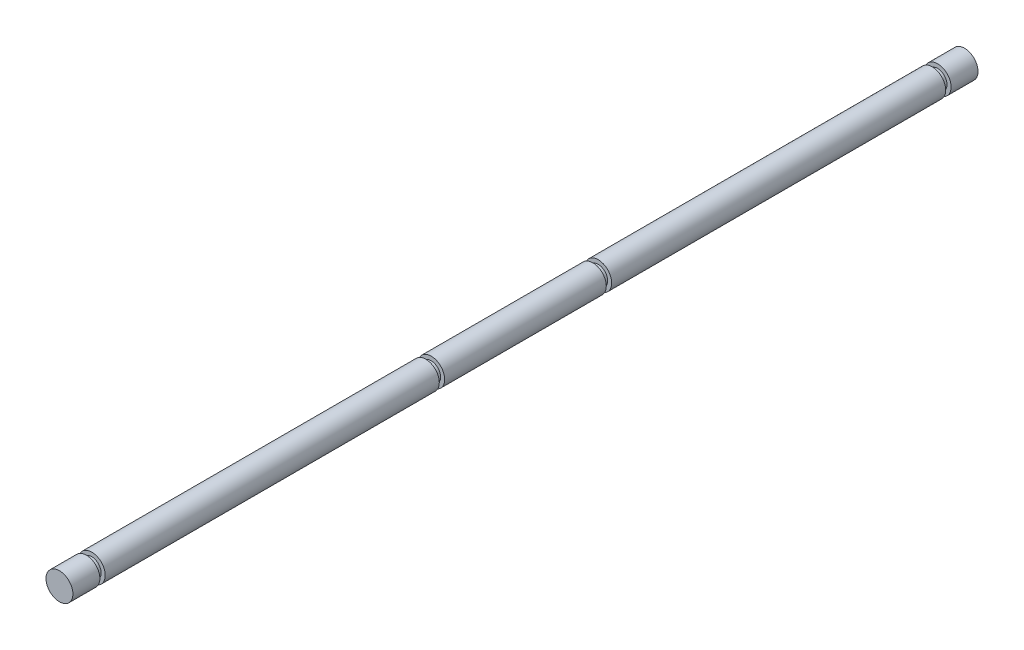
SolidWorks part; units mm, degrees
ref_plane "前视基准面" through (0, 0, 0) normal (0, 0, 1) x (1, 0, 0)
ref_plane "上视基准面" through (0, 0, 0) normal (0, 1, 0) x (1, 0, 0)
ref_plane "右视基准面" through (0, 0, 0) normal (1, 0, 0) x (0, 0, -1)
sketch "草图1" plane through (0, 0, 0) normal (0, 0, 1) x (1, 0, 0)
  circle A0 centre (0, 0) radius 5
  dimension "D1" = 10
extrude "凸台-拉伸1" add sketch "草图1" along normal blind 60
sketch "草图2" plane through (0, 0, 60) normal (0, 0, 1) x (1, 0, 0)
  circle A0 centre (0, 0) radius 3.5
  dimension "D1" = 7
extrude "凸台-拉伸2" add sketch "草图2" along normal blind 2
sketch "草图3" plane through (0, 0, 0) normal (0, 0, -1) x (-1, 0, 0)
  circle A0 centre (0, 0) radius 3.5
  dimension "D1" = 7
extrude "凸台-拉伸3" add sketch "草图3" along normal blind 2
sketch "草图4" plane through (0, 0, -2) normal (0, 0, -1) x (-1, 0, 0)
  circle A0 centre (0, 0) radius 5
  dimension "D1" = 10
extrude "凸台-拉伸4" add sketch "草图4" along normal blind 124
sketch "草图5" plane through (0, 0, 62) normal (0, 0, 1) x (1, 0, 0)
  circle A0 centre (0, 0) radius 5
  dimension "D1" = 10
extrude "凸台-拉伸5" add sketch "草图5" along normal blind 124
sketch "草图6" plane through (0, 0, 186) normal (0, 0, 1) x (1, 0, 0)
  circle A0 centre (0, 0) radius 3.5
  dimension "D1" = 7
extrude "凸台-拉伸6" add sketch "草图6" along normal blind 2
sketch "草图7" plane through (0, 0, 188) normal (0, 0, 1) x (1, 0, 0)
  circle A0 centre (0, 0) radius 5
  dimension "D1" = 10
extrude "凸台-拉伸7" add sketch "草图7" along normal blind 10
sketch "草图8" plane through (0, 0, -126) normal (0, 0, -1) x (-1, 0, 0)
  circle A0 centre (0, 0) radius 3.5
  dimension "D1" = 7
extrude "凸台-拉伸8" add sketch "草图8" along normal blind 2
sketch "草图9" plane through (0, 0, -128) normal (0, 0, -1) x (-1, 0, 0)
  circle A0 centre (0, 0) radius 5
  dimension "D1" = 10
extrude "凸台-拉伸9" add sketch "草图9" along normal blind 10
